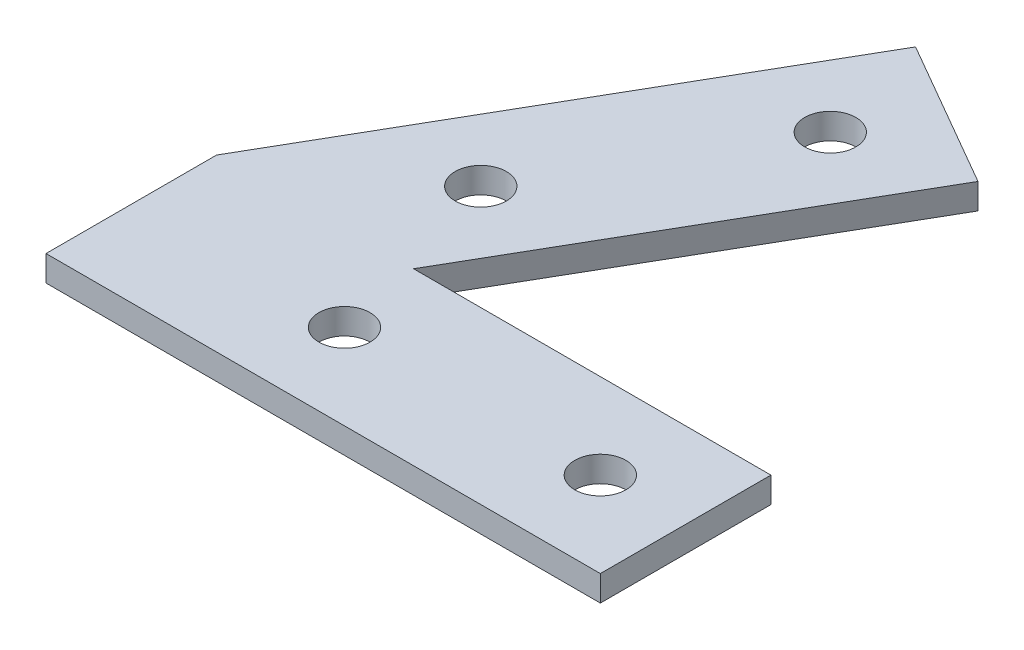
SolidWorks part; units mm, degrees
ref_plane "前视基准面" through (0, 0, 0) normal (0, 0, 1) x (1, 0, 0)
ref_plane "上视基准面" through (0, 0, 0) normal (0, 1, 0) x (1, 0, 0)
ref_plane "右视基准面" through (0, 0, 0) normal (1, 0, 0) x (0, 0, -1)
other "Configuration Table"
sketch "草图1" plane through (0, 0, 0) normal (0, 1, 0) x (1, 0, 0)
  line L0 (0, 0) -> (0, 20)
  line L1 (0, 0) -> (65, 0)
  line L2 (65, 0) -> (65, 20)
  line L3 (65, 20) -> (23.094, 20)
  line L4 (23.094, 20) -> (47.3205, 61.9615)
  line L5 (47.3205, 61.9615) -> (30, 71.9615)
  line L6 (30, 71.9615) -> (0, 20)
  line L7 (38.6603, 66.9615) -> (24.6489, 42.6931) construction
  line L8 (24.6489, 42.6931) -> (25.9562, 44.9574)
  line L9 (65, 10) -> (47.3205, 10) construction
  line L10 (65, 10) -> (55, 10)
  line L11 (55, 10) -> (25, 10)
  line L12 (25, 10) -> (5.7735, 10)
  line L13 (38.6603, 66.9615) -> (33.6603, 58.3013)
  line L14 (33.6603, 58.3013) -> (18.6603, 32.3205)
  circle A0 centre (18.6603, 32.3205) radius 3
  circle A1 centre (33.6603, 58.3013) radius 3
  circle A2 centre (25, 10) radius 3
  circle A3 centre (55, 10) radius 3
  dimension "D11" = 6
  dimension "D1" = 65
  dimension "D2" = 60
  dimension "D3" = 20
  dimension "D4" = 20
  dimension "D5" = 60
  dimension "D6" = 20
  dimension "D7" = 10
  dimension "D8" = 30
  dimension "D9" = 10
  dimension "D10" = 30
extrude "凸台-拉伸1" add sketch "草图1" along normal blind 3
equation "\"a\" = 20'mm"
equation "\"b\"= 20"
